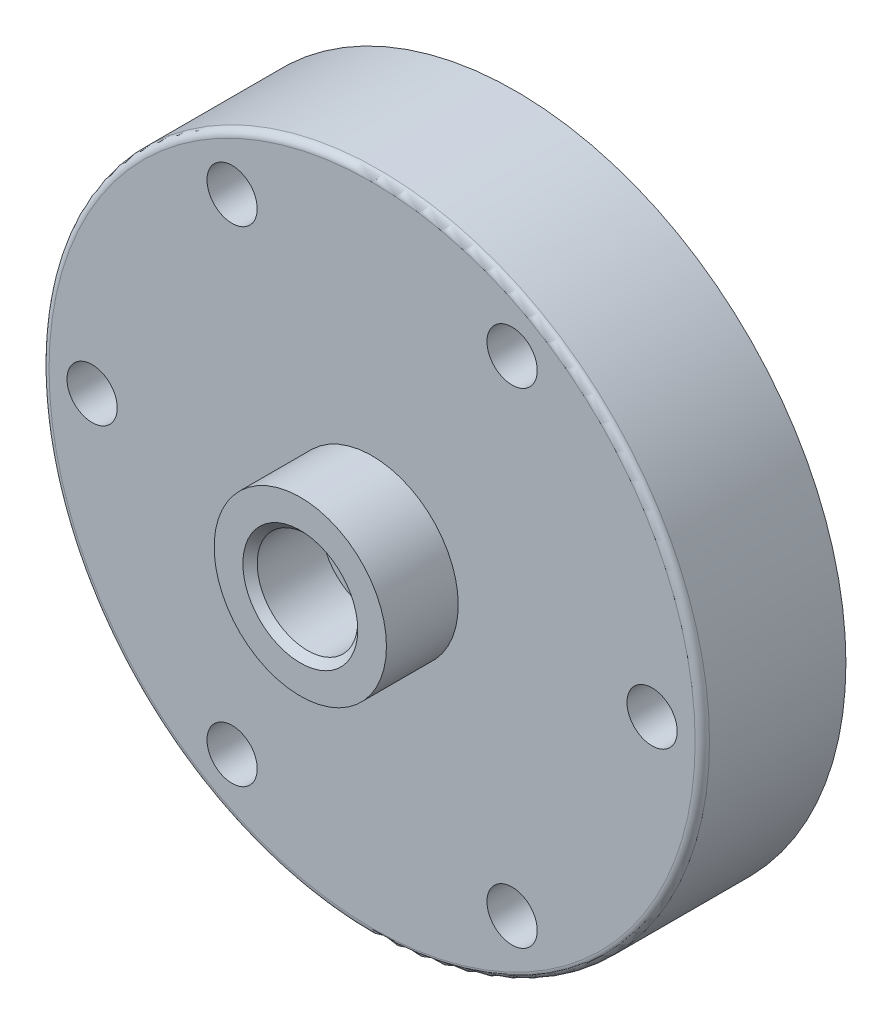
SolidWorks part; units mm, degrees
ref_plane "Front Plane" through (0, 0, 0) normal (0, 0, 1) x (1, 0, 0)
ref_plane "Top Plane" through (0, 0, 0) normal (0, 1, 0) x (1, 0, 0)
ref_plane "Right Plane" through (0, 0, 0) normal (1, 0, 0) x (0, 0, -1)
sketch "Sketch1" plane through (0, 0, 0) normal (0, 0, 1) x (1, 0, 0)
  circle A0 centre (0, 0) radius 46
  dimension "D1" = 92
extrude "Boss-Extrude1" add sketch "Sketch1" along normal mid plane 20
sketch "Sketch2" plane through (0, 0, 10) normal (0, 0, 1) x (1, 0, 0)
  circle A0 centre (0, 0) radius 12
  dimension "D1" = 24
extrude "Boss-Extrude2" add sketch "Sketch2" along normal blind 10
sketch "Sketch3" plane through (0, 0, 10) normal (0, 0, 1) x (1, 0, 0)
  line L0 (0, 0) -> (0, 62.3056) construction
  line L1 (0, 0) -> (66.6237, 0) construction
  circle A0 centre (0, 0) radius 39 construction
  circle A1 centre (39, 0) radius 3.5
  circle A2 centre (19.5, -33.775) radius 3.5
  circle A3 centre (-19.5, -33.775) radius 3.5
  circle A4 centre (-39, 0) radius 3.5
  circle A5 centre (-19.5, 33.775) radius 3.5
  circle A6 centre (19.5, 33.775) radius 3.5
  point P20 (0, 0)
  dimension "D1" = 78
  dimension "D2" = 7
  dimension "D3" = 6
extrude "Cut-Extrude1" cut sketch "Sketch3" against normal through all
fillet "Fillet2" radius 1 1 edges at (46, 0, 10)
sketch "Sketch4" plane through (0, 0, -10) normal (0, 0, -1) x (-1, 0, 0)
  circle A0 centre (0, 0) radius 33
  dimension "D1" = 66
extrude "Cut-Extrude2" cut sketch "Sketch4" against normal blind 14
sketch "Sketch9" plane through (0, 0, 20) normal (0, 0, 1) x (1, 0, 0)
  circle A0 centre (0, 0) radius 7
  dimension "D1" = 14
extrude "Cut-Extrude3" cut sketch "Sketch9" against normal blind 10
cosmetic thread "Cosmetic Thread1" parameters "D1"=10, "D2"=16
sketch "Sketch10" plane through (0, 0, 10) normal (0, 0, 1) x (1, 0, 0)
  circle A0 centre (0, 0) radius 2.5
  dimension "D1" = 5
extrude "Cut-Extrude4" cut sketch "Sketch10" against normal through all
chamfer "Chamfer1" distance 1 angle 45 1 edges at (7, 0, 20)
sketch "Sketch12" plane through (0, 0, 0) normal (0, 1, 0) x (1, 0, 0)
  line L0 (46, 10) -> (-46, 10) construction
  circle A0 centre (0, 2) radius 4
  dimension "D2" = 8
  dimension "D1" = 8
extrude "Cut-Extrude7" cut sketch "Sketch12" against normal blind 100
